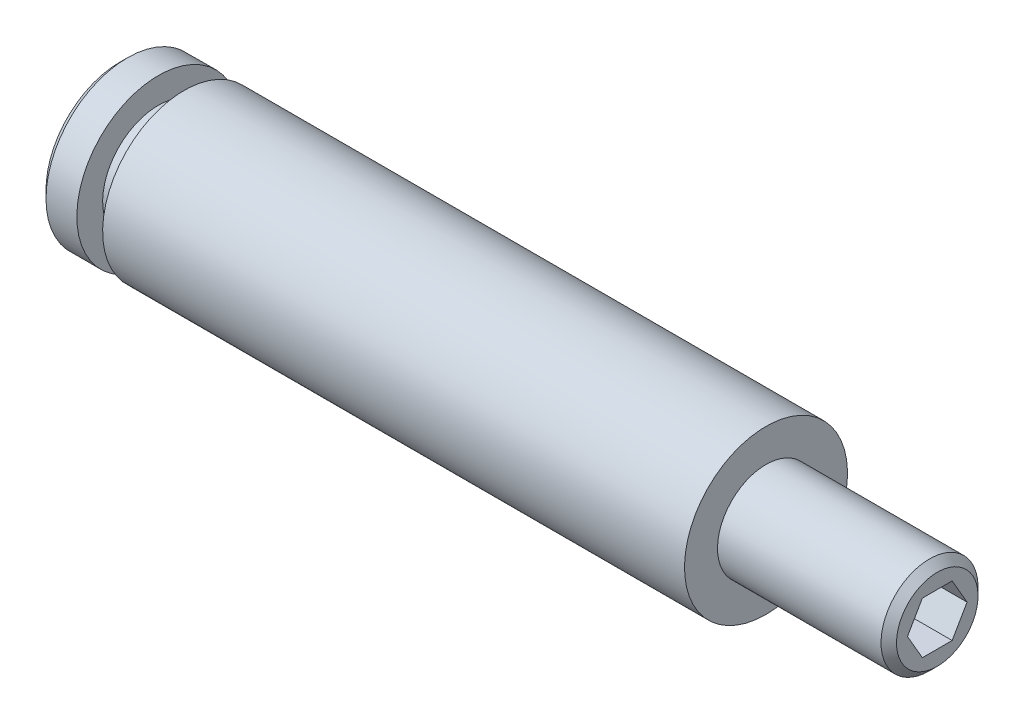
SolidWorks part; units mm, degrees
material "AISI 316 Annealed Stainless Steel Bar (SS)"
ref_plane "Front Plane" through (0, 0, 0) normal (0, 0, 1) x (1, 0, 0)
ref_plane "Top Plane" through (0, 0, 0) normal (0, 1, 0) x (1, 0, 0)
ref_plane "Right Plane" through (0, 0, 0) normal (1, 0, 0) x (0, 0, -1)
sketch "Sketch1" plane through (0, 0, 0) normal (0, 0, 1) x (1, 0, 0)
  line L0 (0, 0) -> (100.6348, 0)
  line L1 (55, 0) -> (-55, 0) construction
  line L2 (100.6348, 0) -> (100.6348, 5.969)
  line L3 (100.6348, 5.969) -> (79.5528, 5.969)
  line L4 (79.5528, 5.969) -> (79.5528, 10.033)
  line L5 (79.5528, 10.033) -> (7.9248, 10.033)
  line L6 (7.9248, 10.033) -> (7.9248, 6.858)
  line L7 (7.9248, 6.858) -> (4.7498, 6.858)
  line L8 (4.7498, 6.858) -> (4.7498, 10.033)
  line L9 (4.7498, 10.033) -> (0, 10.033)
  line L10 (0, -55) -> (0, 55) construction
  line L11 (0, 10.033) -> (0, 0)
  line L12 (0, 0) -> (100.6348, 0) construction
  dimension "D1" = 3.175
  dimension "D2" = 5.969
  dimension "D3" = 21.082
  dimension "D4" = 71.628
  dimension "D5" = 4.7498
  dimension "D6" = 6.858
  dimension "D7" = 10.033
revolve "Revolve1" add sketch "Sketch1" angle 360 about L12
sketch "Sketch2" plane through (100.6348, 0, 0) normal (1, 0, 0) x (0, 0, -1)
  line L1 (3.6662, 0) -> (1.8331, 3.175)
  line L2 (1.8331, 3.175) -> (-1.8331, 3.175)
  line L3 (-1.8331, 3.175) -> (-3.6662, 0)
  line L4 (-3.6662, 0) -> (-1.8331, -3.175)
  line L5 (-1.8331, -3.175) -> (1.8331, -3.175)
  line L6 (1.8331, -3.175) -> (3.6662, 0)
  circle A0 centre (0, 0) radius 3.175 construction
  dimension "D1" = 6.35
extrude "Cut-Extrude1" cut sketch "Sketch2" against normal blind 9.525
chamfer "Chamfer1" distance 0.9525 angle 45 2 edges at (0, -10.033, 0) (100.6348, -5.969, 0)
